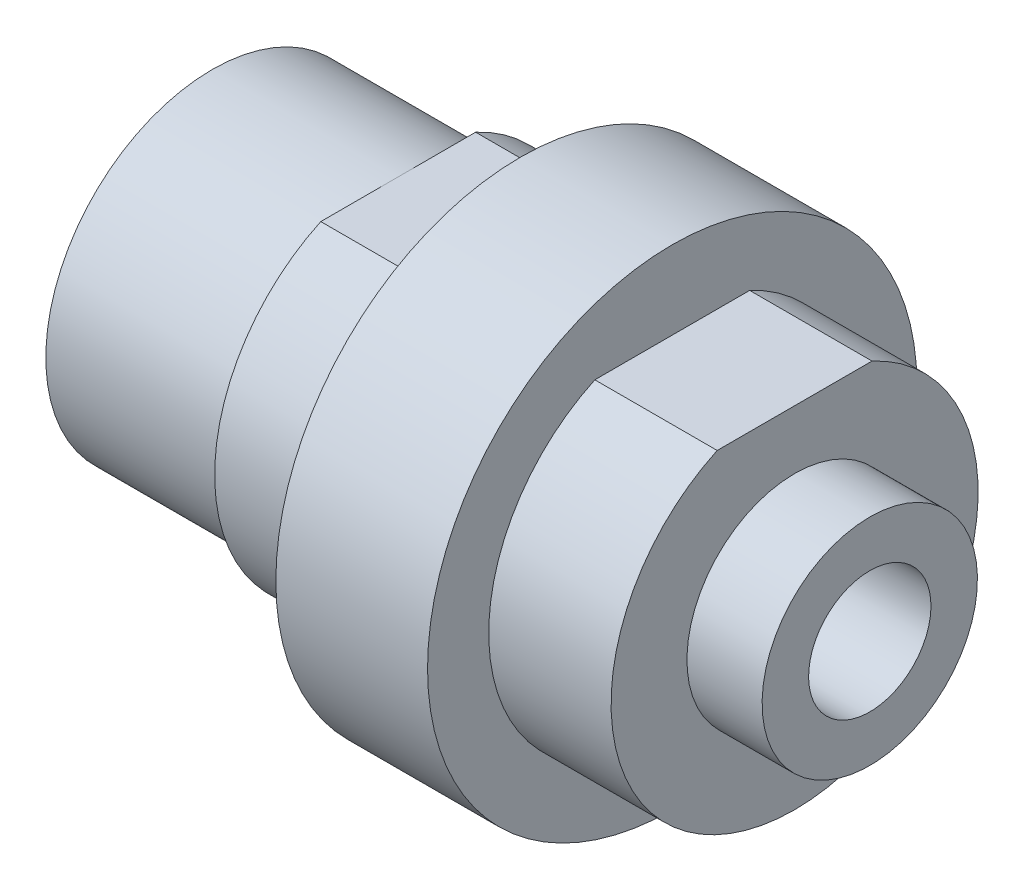
SolidWorks part; units mm, degrees
ref_plane "Front Plane" through (0, 0, 0) normal (0, 0, 1) x (1, 0, 0)
ref_plane "Top Plane" through (0, 0, 0) normal (0, 1, 0) x (1, 0, 0)
ref_plane "Right Plane" through (0, 0, 0) normal (1, 0, 0) x (0, 0, -1)
sketch "Sketch1" plane through (0, 0, 0) normal (0, 0, 1) x (1, 0, 0)
  line L0 (0, 0) -> (0, 8.636)
  line L1 (0, 8.636) -> (9.652, 8.636)
  line L2 (9.652, 8.636) -> (9.652, 9.525)
  line L3 (9.652, 9.525) -> (16.002, 9.525)
  line L4 (16.002, 9.525) -> (16.002, 12.7)
  line L5 (16.002, 12.7) -> (23.876, 12.7)
  line L6 (23.876, 12.7) -> (23.876, 9.525)
  line L7 (23.876, 9.525) -> (30.226, 9.525)
  line L8 (30.226, 9.525) -> (30.226, 5.588)
  line L9 (30.226, 5.588) -> (34.1274, 5.588)
  line L10 (34.1274, 5.588) -> (34.1274, 0)
  line L11 (34.1274, 0) -> (0, 0)
  line L12 (34.1274, 3.175) -> (0, 3.175)
  line L13 (34.1274, 0) -> (34.1274, 3.175)
  dimension "D1" = 9.652
  dimension "D2" = 6.35
  dimension "D3" = 7.874
  dimension "D4" = 6.35
  dimension "D5" = 3.9014
  dimension "D6" = 3.937
  dimension "D7" = 3.175
  dimension "D8" = 3.175
  dimension "D9" = 0.889
  dimension "D10" = 8.636
  dimension "D11" = 3.175
revolve "Revolve1" add sketch "Sketch1" angle 360 about L11
sketch "Sketch2" plane through (0, 0, 0) normal (0, 0, 1) x (1, 0, 0)
  line L0 (9.652, 9.525) -> (9.652, 8.636)
  line L1 (9.652, 8.636) -> (16.002, 8.636)
  line L2 (16.002, 9.525) -> (16.002, -9.525) construction
  line L3 (16.002, 8.636) -> (16.002, 9.525)
  line L4 (16.002, 9.525) -> (9.652, 9.525)
  line L5 (23.876, 9.525) -> (23.876, 8.636)
  line L6 (23.876, 8.636) -> (30.226, 8.636)
  line L7 (30.226, 8.636) -> (30.226, 9.525)
  line L8 (30.226, 9.525) -> (23.876, 9.525)
  point P14 (30.226, 9.525)
  point P15 (0, 0)
  point P17 (0, 0)
extrude "Cut-Extrude1" cut sketch "Sketch2" against normal through all both and the other way through all
